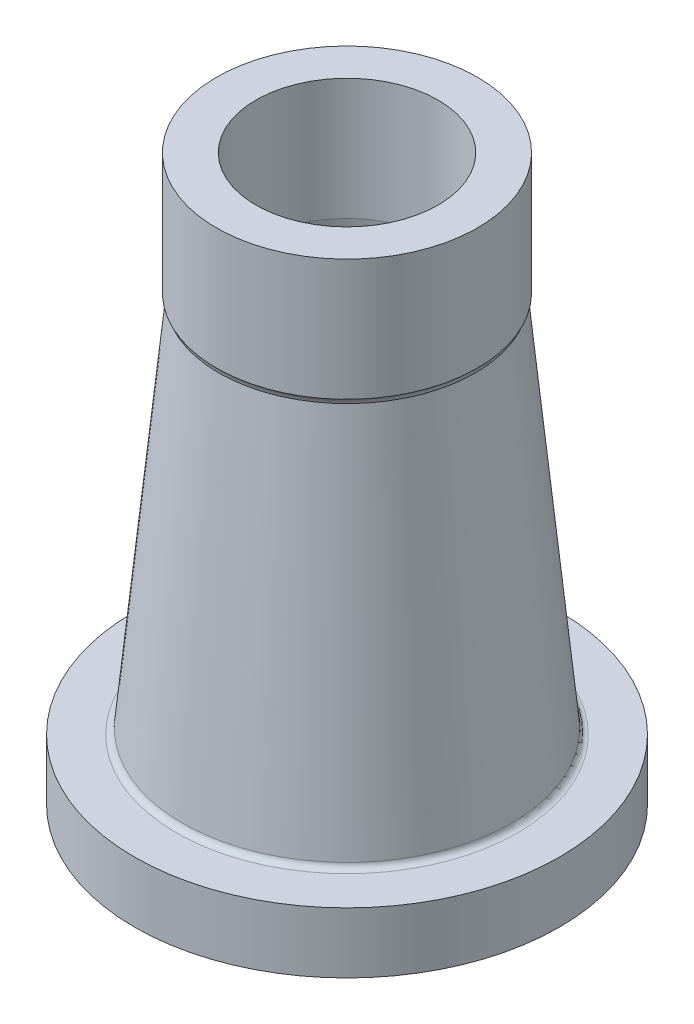
SolidWorks part; units mm, degrees
ref_plane "Front Plane" through (0, 0, 0) normal (0, 0, 1) x (1, 0, 0)
ref_plane "Top Plane" through (0, 0, 0) normal (0, 1, 0) x (1, 0, 0)
ref_plane "Right Plane" through (0, 0, 0) normal (1, 0, 0) x (0, 0, -1)
sketch "Sketch1" plane through (0, 0, 0) normal (0, 0, 1) x (1, 0, 0)
  line L0 (0, 0) -> (0, 186) construction
  line L1 (30, 186) -> (43, 186)
  line L2 (43, 146) -> (43, 186)
  line L4 (56.2068, 20) -> (70, 20)
  line L5 (70, 20) -> (70, 0)
  line L6 (70, 0) -> (50, 0)
  line L7 (50, 0) -> (49.883, 1.1949)
  line L8 (47.8925, 3) -> (44, 3)
  line L9 (44, 3) -> (30, 146)
  line L10 (30, 146) -> (30, 186)
  line L11 (42.2309, 144.2275) -> (54.2163, 21.8051)
  arc A0 (43, 146) -> (42.2309, 144.2275) centre (47.1158, 143.161) ccw
  arc A1 (49.883, 1.1949) -> (47.8925, 3) centre (47.8925, 1) ccw
  arc A2 (54.2163, 21.8051) -> (56.2068, 20) centre (56.2068, 22) ccw
  dimension "D11" = 10
  dimension "D12" = 2
  dimension "D13" = 2
  dimension "D1" = 20
  dimension "D2" = 70
  dimension "D3" = 88
  dimension "D4" = 100
  dimension "D5" = 3
  dimension "D6" = 40
  dimension "D7" = 60
  dimension "D8" = 12
  dimension "D9" = 186
  dimension "D10" = 86
  dimension "D14" = 42.2309
revolve "Revolve1" add sketch "Sketch1" angle 360 about L0
